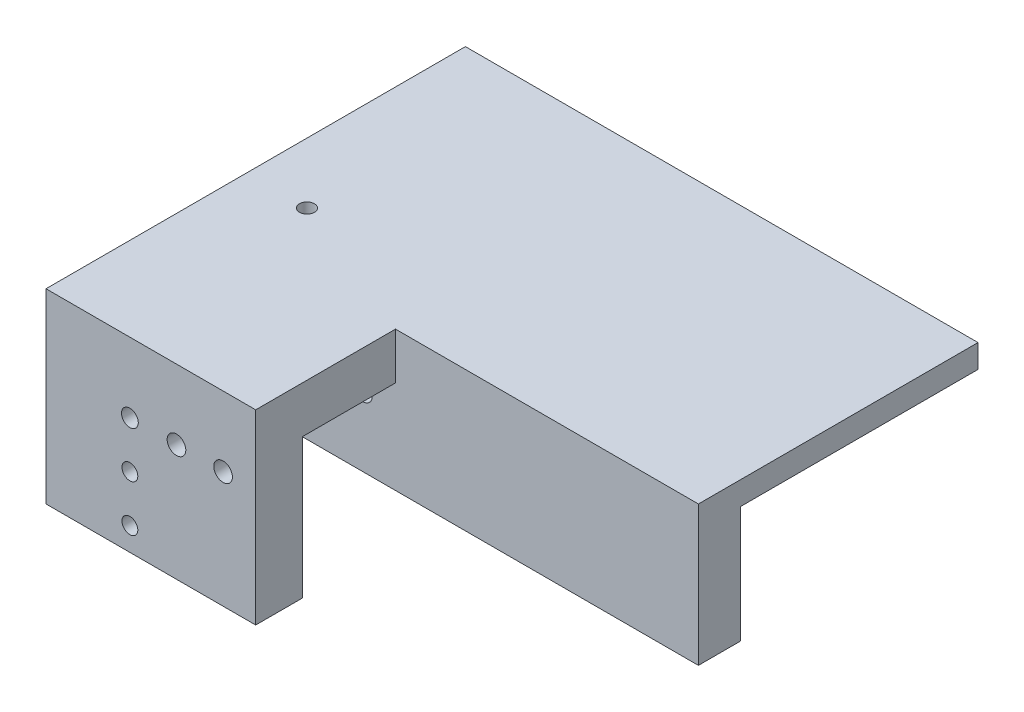
SolidWorks part; units mm, degrees
ref_plane "Front Plane" through (0, 0, 0) normal (0, 0, 1) x (1, 0, 0)
ref_plane "Top Plane" through (0, 0, 0) normal (0, 1, 0) x (1, 0, 0)
ref_plane "Right Plane" through (0, 0, 0) normal (1, 0, 0) x (0, 0, -1)
sketch "Sketch1" plane through (0, 0, 0) normal (0, 1, 0) x (1, 0, 0)
  line L0 (-69.85, -38.1) -> (69.85, -38.1)
  line L1 (-69.85, -38.1) -> (-69.85, 38.1)
  line L2 (69.85, -38.1) -> (69.85, 38.1)
  line L3 (-69.85, 38.1) -> (69.85, 38.1)
  line L4 (-69.85, -38.1) -> (69.85, 38.1) construction
  line L5 (69.85, -38.1) -> (-69.85, 38.1) construction
  point P1 (0, 0)
  dimension "D1" = 139.7
  dimension "D2" = 76.2
extrude "Boss-Extrude1" add sketch "Sketch1" against normal blind 38.1
sketch "Sketch2" plane through (0, -38.1, 0) normal (0, -1, 0) x (1, 0, 0)
  line L0 (69.85, 26.67) -> (7.62, 26.67)
  line L1 (69.85, 38.1) -> (69.85, -38.1) construction
  line L2 (7.62, 26.67) -> (7.62, 0)
  line L3 (7.62, 0) -> (-58.42, 0)
  line L4 (-58.42, 0) -> (-58.42, -38.1)
  line L5 (69.85, -38.1) -> (-69.85, -38.1) construction
  line L6 (-69.85, 38.1) -> (69.85, 38.1) construction
  line L7 (-69.85, -38.1) -> (-69.85, 38.1) construction
  dimension "D1" = 11.43
  dimension "D2" = 77.47
  dimension "D3" = 38.1
  dimension "D4" = 11.43
extrude "Cut-Extrude1" cut sketch "Sketch2" against normal blind 31.75 and the other way through all
sketch "Sketch3" plane through (0, -38.1, 0) normal (0, -1, 0) x (1, 0, 0)
  line L0 (-69.85, -38.1) -> (-69.85, 38.1) construction
  line L1 (-69.85, 38.1) -> (69.85, 38.1) construction
  circle A0 centre (-53.34, 21.59) radius 2.032
  dimension "D1" = 4.064
  dimension "D2" = 16.51
  dimension "D3" = 16.51
extrude "Cut-Extrude2" cut sketch "Sketch3" against normal through all
sketch "Sketch4" plane through (0, 0, 0) normal (0, 0, -1) x (-1, 0, 0)
  line L0 (-7.62, -38.1) -> (-7.62, -6.35) construction
  line L1 (58.42, -6.35) -> (6.35, -6.35)
  line L2 (58.42, -6.35) -> (58.42, -31.75)
  line L3 (58.42, -31.75) -> (6.35, -31.75)
  line L4 (6.35, -6.35) -> (6.35, -31.75)
  line L5 (-7.62, -38.1) -> (58.42, -38.1) construction
  dimension "D1" = 13.97
  dimension "D2" = 6.35
extrude "Cut-Extrude3" cut sketch "Sketch4" against normal blind 10.414
sketch "Sketch7" plane through (0, 0, 38.1) normal (0, 0, 1) x (1, 0, 0)
  line L1 (-69.85, 0) -> (-12.7, 0)
  line L2 (-69.85, 0) -> (-69.85, -12.7)
  line L3 (-69.85, -12.7) -> (-12.7, -12.7)
  line L4 (-12.7, 0) -> (-12.7, -12.7)
  dimension "D1" = 57.15
  dimension "D2" = 12.7
extrude "Boss-Extrude2" add sketch "Sketch7" along normal blind 25.4
sketch "Sketch8" plane through (0, 0, 63.5) normal (0, 0, 1) x (1, 0, 0)
  line L1 (-69.85, 0) -> (-12.7, 0)
  line L2 (-69.85, 0) -> (-69.85, -50.8)
  line L3 (-69.85, -50.8) -> (-12.7, -50.8)
  line L4 (-12.7, 0) -> (-12.7, -50.8)
  dimension "D1" = 50.8
  dimension "D2" = 57.15
extrude "Boss-Extrude3" add sketch "Sketch8" along normal blind 12.7
sketch "Sketch5" plane through (0, 0, 10.414) normal (0, 0, -1) x (-1, 0, 0)
  line L0 (58.42, -31.75) -> (58.42, -6.35) construction
  line L1 (6.35, -31.75) -> (58.42, -31.75) construction
  circle A0 centre (46.99, -19.05) radius 2.286
  circle A1 centre (34.29, -19.05) radius 2.54
  circle A2 centre (21.59, -19.05) radius 2.54
  dimension "D1" = 4.572
  dimension "D4" = 12.7
  dimension "D6" = 5.08
  dimension "D2" = 11.43
  dimension "D3" = 12.7
  dimension "D5" = 12.7
extrude "Cut-Extrude4" cut sketch "Sketch5" against normal through all
sketch "Sketch6" plane through (0, 0, 10.414) normal (0, 0, -1) x (-1, 0, 0)
  line L0 (27.051, -18.288) -> (26.6125, -18.288)
  line L1 (27.051, -21.082) -> (28.829, -21.082)
  line L2 (27.051, -21.082) -> (27.051, -19.812)
  line L3 (27.051, -17.018) -> (28.829, -17.018)
  line L4 (28.829, -21.082) -> (28.829, -19.812)
  line L5 (27.051, -21.082) -> (28.829, -17.018) construction
  line L6 (27.051, -17.018) -> (28.829, -21.082) construction
  line L7 (27.051, -19.812) -> (26.6125, -19.812)
  line L8 (28.829, -19.812) -> (29.2675, -19.812)
  line L9 (28.829, -18.288) -> (29.2675, -18.288)
  line L10 (28.829, -18.288) -> (28.829, -17.018)
  line L11 (27.051, -18.288) -> (27.051, -17.018)
  arc A0 (29.2675, -19.812) -> (29.2675, -18.288) centre (34.29, -19.05) ccw
  arc A1 (26.6125, -18.288) -> (26.6125, -19.812) centre (21.59, -19.05) ccw
  point P6 (27.94, -19.05)
  dimension "D1" = 10.16
  dimension "D2" = 1.778
  dimension "D3" = 4.064
  dimension "D4" = 1.27
extrude "Cut-Extrude5" cut sketch "Sketch6" against normal blind 14.986
sketch "Sketch9" plane through (0, 0, 63.5) normal (0, 0, -1) x (-1, 0, 0)
  line L0 (46.99, -19.05) -> (46.99, -50019.05) construction
  line L1 (69.85, -50.8) -> (12.7, -50.8) construction
  line L2 (42.3232, -16.8654) -> (42.3232, -46.6346)
  line L3 (44.704, -14.224) -> (42.3232, -16.8654)
  line L4 (51.6568, -16.8654) -> (51.6568, -46.6346)
  line L5 (42.3232, -31.75) -> (51.6568, -31.75) construction
  line L6 (49.276, -49.276) -> (44.704, -49.276)
  line L7 (51.6568, -16.8654) -> (49.276, -14.224)
  line L8 (49.276, -14.224) -> (44.704, -14.224)
  line L9 (51.6568, -46.6346) -> (49.276, -49.276)
  line L10 (44.704, -49.276) -> (42.3232, -46.6346)
  circle A1 centre (46.99, -19.05) radius 2.286 construction
  point P5 (46.99, -14.224)
  dimension "D1" = 90
  dimension "D5" = 3.556
  dimension "D6" = 4.826
  dimension "D2" = 4.572
  dimension "D3" = 47.97
  dimension "D4" = 35.052
extrude "Cut-Extrude6" cut sketch "Sketch9" against normal blind 7.112
sketch "Sketch10" plane through (0, 0, 70.612) normal (0, 0, -1) x (-1, 0, 0)
  line L0 (46.99, -49.276) -> (46.99, -14.224) construction
  line L1 (44.704, -49.276) -> (49.276, -49.276) construction
  line L2 (49.276, -14.224) -> (44.704, -14.224) construction
  line L3 (46.99, -19.05) -> (40.64, -19.05) construction
  line L4 (46.99, -19.05) -> (46.99, -30.0482) construction
  circle A0 centre (46.99, -19.05) radius 2.159
  circle A3 centre (46.99, -31.75) radius 2.159
  circle A6 centre (46.99, -44.45) radius 2.159
  circle A9 centre (46.99, -31.75) radius 2.159 [skipped]
  circle A10 centre (46.99, -19.05) radius 2.159 [skipped]
  circle A11 centre (46.99, -19.05) radius 2.159 [skipped]
  circle A12 centre (46.99, -31.75) radius 2.159 [skipped]
  circle A13 centre (46.99, -44.45) radius 2.159 [skipped]
  circle A14 centre (46.99, -44.45) radius 2.159 [skipped]
  dimension "D1" = 3
  dimension "D4" = 4.318
  dimension "D2" = 90
  dimension "D3" = 3
extrude "Cut-Extrude7" cut sketch "Sketch10" against normal through all
sketch "Sketch11" plane through (0, 0, 0) normal (0, 0, -1) x (-1, 0, 0)
  line L1 (58.42, -38.1) -> (6.35, -38.1)
  line L2 (58.42, -38.1) -> (58.42, -31.75)
  line L3 (58.42, -31.75) -> (6.35, -31.75)
  line L4 (6.35, -38.1) -> (6.35, -31.75)
extrude "Boss-Extrude4" add sketch "Sketch11" along normal blind 25.4
